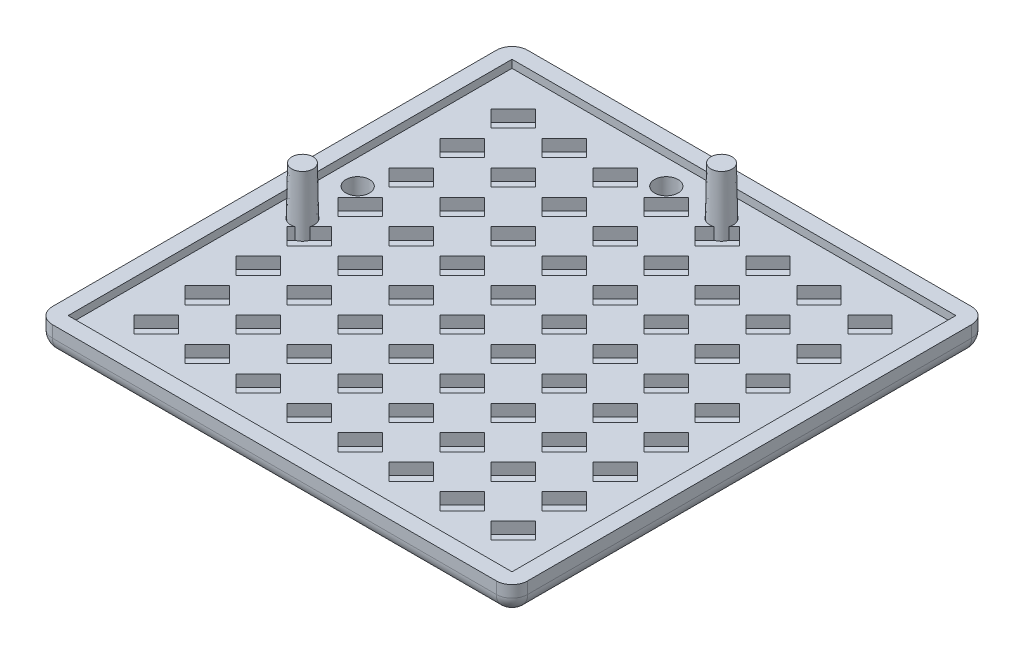
SolidWorks part; units mm, degrees
ref_plane "Front Plane" through (0, 0, 0) normal (0, 0, 1) x (1, 0, 0)
ref_plane "Top Plane" through (0, 0, 0) normal (0, 1, 0) x (1, 0, 0)
ref_plane "Right Plane" through (0, 0, 0) normal (1, 0, 0) x (0, 0, -1)
sketch "Sketch1" plane through (0, 0, 0) normal (0, 1, 0) x (1, 0, 0)
  line L1 (-30.3, -30.3) -> (30.3, -30.3)
  line L2 (-30.3, -30.3) -> (-30.3, 30.3)
  line L3 (-30.3, 30.3) -> (30.3, 30.3)
  line L4 (30.3, -30.3) -> (30.3, 30.3)
  line L5 (-30.3, -30.3) -> (30.3, 30.3) construction
  line L6 (-30.3, 30.3) -> (30.3, -30.3) construction
  point P0 (0, 0)
  dimension "D1" = 60.6
  dimension "D2" = 60.6
extrude "Boss-Extrude1" add sketch "Sketch1" along normal blind 3.5
sketch "led" plane through (0, 0, 0) normal (0, -1, 0) x (1, 0, 0)
  line L0 (30.3, -30.3) -> (-30.3, 30.3) construction
  line L1 (-30.3, 30.3) -> (-30.3, -30.3) construction
  line L2 (-30.3, -30.3) -> (30.3, 30.3) construction
  line L3 (22.4716, -20.3503) -> (25.3, -23.1787)
  line L4 (22.4716, -20.3503) -> (20.3503, -22.4716)
  line L5 (25.3, -23.1787) -> (23.1787, -25.3)
  line L6 (20.3503, -22.4716) -> (23.1787, -25.3)
  line L7 (22.4716, -20.3503) -> (23.1787, -25.3) construction
  line L8 (25.3, -23.1787) -> (20.3503, -22.4716) construction
  line L11 (30.3, 30.3) -> (30.3, -30.3) construction
  line L13 (13.8503, -22.4716) -> (16.6787, -25.3)
  line L14 (15.9716, -20.3503) -> (18.8, -23.1787)
  line L15 (15.9716, -20.3503) -> (13.8503, -22.4716)
  line L16 (18.8, -23.1787) -> (16.6787, -25.3)
  line L17 (7.3503, -22.4716) -> (10.1787, -25.3)
  line L18 (9.4716, -20.3503) -> (12.3, -23.1787)
  line L19 (9.4716, -20.3503) -> (7.3503, -22.4716)
  line L20 (12.3, -23.1787) -> (10.1787, -25.3)
  line L21 (0.8503, -22.4716) -> (3.6787, -25.3)
  line L22 (2.9716, -20.3503) -> (5.8, -23.1787)
  line L23 (2.9716, -20.3503) -> (0.8503, -22.4716)
  line L24 (5.8, -23.1787) -> (3.6787, -25.3)
  line L25 (-5.6497, -22.4716) -> (-2.8213, -25.3)
  line L26 (-3.5284, -20.3503) -> (-0.7, -23.1787)
  line L27 (-3.5284, -20.3503) -> (-5.6497, -22.4716)
  line L28 (-0.7, -23.1787) -> (-2.8213, -25.3)
  line L29 (-12.1497, -22.4716) -> (-9.3213, -25.3)
  line L30 (-10.0284, -20.3503) -> (-7.2, -23.1787)
  line L31 (-10.0284, -20.3503) -> (-12.1497, -22.4716)
  line L32 (-7.2, -23.1787) -> (-9.3213, -25.3)
  line L33 (-18.6497, -22.4716) -> (-15.8213, -25.3)
  line L34 (-16.5284, -20.3503) -> (-13.7, -23.1787)
  line L35 (-16.5284, -20.3503) -> (-18.6497, -22.4716)
  line L36 (-13.7, -23.1787) -> (-15.8213, -25.3)
  line L37 (-25.1497, -22.4716) -> (-22.3213, -25.3)
  line L38 (-23.0284, -20.3503) -> (-20.2, -23.1787)
  line L39 (-23.0284, -20.3503) -> (-25.1497, -22.4716)
  line L40 (-20.2, -23.1787) -> (-22.3213, -25.3)
  line L41 (13.8503, -15.9716) -> (16.6787, -18.8)
  line L42 (15.9716, -13.8503) -> (18.8, -16.6787)
  line L43 (15.9716, -13.8503) -> (13.8503, -15.9716)
  line L44 (18.8, -16.6787) -> (16.6787, -18.8)
  line L45 (7.3503, -15.9716) -> (10.1787, -18.8)
  line L46 (9.4716, -13.8503) -> (12.3, -16.6787)
  line L47 (9.4716, -13.8503) -> (7.3503, -15.9716)
  line L48 (12.3, -16.6787) -> (10.1787, -18.8)
  line L49 (0.8503, -15.9716) -> (3.6787, -18.8)
  line L50 (2.9716, -13.8503) -> (5.8, -16.6787)
  line L51 (2.9716, -13.8503) -> (0.8503, -15.9716)
  line L52 (5.8, -16.6787) -> (3.6787, -18.8)
  line L53 (-5.6497, -15.9716) -> (-2.8213, -18.8)
  line L54 (-3.5284, -13.8503) -> (-0.7, -16.6787)
  line L55 (-3.5284, -13.8503) -> (-5.6497, -15.9716)
  line L56 (-0.7, -16.6787) -> (-2.8213, -18.8)
  line L57 (-12.1497, -15.9716) -> (-9.3213, -18.8)
  line L58 (-10.0284, -13.8503) -> (-7.2, -16.6787)
  line L59 (-10.0284, -13.8503) -> (-12.1497, -15.9716)
  line L60 (-7.2, -16.6787) -> (-9.3213, -18.8)
  line L61 (-18.6497, -15.9716) -> (-15.8213, -18.8)
  line L62 (-16.5284, -13.8503) -> (-13.7, -16.6787)
  line L63 (-16.5284, -13.8503) -> (-18.6497, -15.9716)
  line L64 (-13.7, -16.6787) -> (-15.8213, -18.8)
  line L65 (-25.1497, -15.9716) -> (-22.3213, -18.8)
  line L66 (-23.0284, -13.8503) -> (-20.2, -16.6787)
  line L67 (-23.0284, -13.8503) -> (-25.1497, -15.9716)
  line L68 (-20.2, -16.6787) -> (-22.3213, -18.8)
  line L69 (13.8503, -9.4716) -> (16.6787, -12.3)
  line L70 (15.9716, -7.3503) -> (18.8, -10.1787)
  line L71 (15.9716, -7.3503) -> (13.8503, -9.4716)
  line L72 (18.8, -10.1787) -> (16.6787, -12.3)
  line L73 (7.3503, -9.4716) -> (10.1787, -12.3)
  line L74 (9.4716, -7.3503) -> (12.3, -10.1787)
  line L75 (9.4716, -7.3503) -> (7.3503, -9.4716)
  line L76 (12.3, -10.1787) -> (10.1787, -12.3)
  line L77 (0.8503, -9.4716) -> (3.6787, -12.3)
  line L78 (2.9716, -7.3503) -> (5.8, -10.1787)
  line L79 (2.9716, -7.3503) -> (0.8503, -9.4716)
  line L80 (5.8, -10.1787) -> (3.6787, -12.3)
  line L81 (-5.6497, -9.4716) -> (-2.8213, -12.3)
  line L82 (-3.5284, -7.3503) -> (-0.7, -10.1787)
  line L83 (-3.5284, -7.3503) -> (-5.6497, -9.4716)
  line L84 (-0.7, -10.1787) -> (-2.8213, -12.3)
  line L85 (-12.1497, -9.4716) -> (-9.3213, -12.3)
  line L86 (-10.0284, -7.3503) -> (-7.2, -10.1787)
  line L87 (-10.0284, -7.3503) -> (-12.1497, -9.4716)
  line L88 (-7.2, -10.1787) -> (-9.3213, -12.3)
  line L89 (-18.6497, -9.4716) -> (-15.8213, -12.3)
  line L90 (-16.5284, -7.3503) -> (-13.7, -10.1787)
  line L91 (-16.5284, -7.3503) -> (-18.6497, -9.4716)
  line L92 (-13.7, -10.1787) -> (-15.8213, -12.3)
  line L93 (-25.1497, -9.4716) -> (-22.3213, -12.3)
  line L94 (-23.0284, -7.3503) -> (-20.2, -10.1787)
  line L95 (-23.0284, -7.3503) -> (-25.1497, -9.4716)
  line L96 (-20.2, -10.1787) -> (-22.3213, -12.3)
  line L97 (13.8503, -2.9716) -> (16.6787, -5.8)
  line L98 (15.9716, -0.8503) -> (18.8, -3.6787)
  line L99 (15.9716, -0.8503) -> (13.8503, -2.9716)
  line L100 (18.8, -3.6787) -> (16.6787, -5.8)
  line L101 (7.3503, -2.9716) -> (10.1787, -5.8)
  line L102 (9.4716, -0.8503) -> (12.3, -3.6787)
  line L103 (9.4716, -0.8503) -> (7.3503, -2.9716)
  line L104 (12.3, -3.6787) -> (10.1787, -5.8)
  line L105 (0.8503, -2.9716) -> (3.6787, -5.8)
  line L106 (2.9716, -0.8503) -> (5.8, -3.6787)
  line L107 (2.9716, -0.8503) -> (0.8503, -2.9716)
  line L108 (5.8, -3.6787) -> (3.6787, -5.8)
  line L109 (-5.6497, -2.9716) -> (-2.8213, -5.8)
  line L110 (-3.5284, -0.8503) -> (-0.7, -3.6787)
  line L111 (-3.5284, -0.8503) -> (-5.6497, -2.9716)
  line L112 (-0.7, -3.6787) -> (-2.8213, -5.8)
  line L113 (-12.1497, -2.9716) -> (-9.3213, -5.8)
  line L114 (-10.0284, -0.8503) -> (-7.2, -3.6787)
  line L115 (-10.0284, -0.8503) -> (-12.1497, -2.9716)
  line L116 (-7.2, -3.6787) -> (-9.3213, -5.8)
  line L117 (-18.6497, -2.9716) -> (-15.8213, -5.8)
  line L118 (-16.5284, -0.8503) -> (-13.7, -3.6787)
  line L119 (-16.5284, -0.8503) -> (-18.6497, -2.9716)
  line L120 (-13.7, -3.6787) -> (-15.8213, -5.8)
  line L121 (-25.1497, -2.9716) -> (-22.3213, -5.8)
  line L122 (-23.0284, -0.8503) -> (-20.2, -3.6787)
  line L123 (-23.0284, -0.8503) -> (-25.1497, -2.9716)
  line L124 (-20.2, -3.6787) -> (-22.3213, -5.8)
  line L125 (13.8503, 3.5284) -> (16.6787, 0.7)
  line L126 (15.9716, 5.6497) -> (18.8, 2.8213)
  line L127 (15.9716, 5.6497) -> (13.8503, 3.5284)
  line L128 (18.8, 2.8213) -> (16.6787, 0.7)
  line L129 (7.3503, 3.5284) -> (10.1787, 0.7)
  line L130 (9.4716, 5.6497) -> (12.3, 2.8213)
  line L131 (9.4716, 5.6497) -> (7.3503, 3.5284)
  line L132 (12.3, 2.8213) -> (10.1787, 0.7)
  line L133 (0.8503, 3.5284) -> (3.6787, 0.7)
  line L134 (2.9716, 5.6497) -> (5.8, 2.8213)
  line L135 (2.9716, 5.6497) -> (0.8503, 3.5284)
  line L136 (5.8, 2.8213) -> (3.6787, 0.7)
  line L137 (-5.6497, 3.5284) -> (-2.8213, 0.7)
  line L138 (-3.5284, 5.6497) -> (-0.7, 2.8213)
  line L139 (-3.5284, 5.6497) -> (-5.6497, 3.5284)
  line L140 (-0.7, 2.8213) -> (-2.8213, 0.7)
  line L141 (-12.1497, 3.5284) -> (-9.3213, 0.7)
  line L142 (-10.0284, 5.6497) -> (-7.2, 2.8213)
  line L143 (-10.0284, 5.6497) -> (-12.1497, 3.5284)
  line L144 (-7.2, 2.8213) -> (-9.3213, 0.7)
  line L145 (-18.6497, 3.5284) -> (-15.8213, 0.7)
  line L146 (-16.5284, 5.6497) -> (-13.7, 2.8213)
  line L147 (-16.5284, 5.6497) -> (-18.6497, 3.5284)
  line L148 (-13.7, 2.8213) -> (-15.8213, 0.7)
  line L149 (-25.1497, 3.5284) -> (-22.3213, 0.7)
  line L150 (-23.0284, 5.6497) -> (-20.2, 2.8213)
  line L151 (-23.0284, 5.6497) -> (-25.1497, 3.5284)
  line L152 (-20.2, 2.8213) -> (-22.3213, 0.7)
  line L153 (13.8503, 10.0284) -> (16.6787, 7.2)
  line L154 (15.9716, 12.1497) -> (18.8, 9.3213)
  line L155 (15.9716, 12.1497) -> (13.8503, 10.0284)
  line L156 (18.8, 9.3213) -> (16.6787, 7.2)
  line L157 (7.3503, 10.0284) -> (10.1787, 7.2)
  line L158 (9.4716, 12.1497) -> (12.3, 9.3213)
  line L159 (9.4716, 12.1497) -> (7.3503, 10.0284)
  line L160 (12.3, 9.3213) -> (10.1787, 7.2)
  line L161 (0.8503, 10.0284) -> (3.6787, 7.2)
  line L162 (2.9716, 12.1497) -> (5.8, 9.3213)
  line L163 (2.9716, 12.1497) -> (0.8503, 10.0284)
  line L164 (5.8, 9.3213) -> (3.6787, 7.2)
  line L165 (-5.6497, 10.0284) -> (-2.8213, 7.2)
  line L166 (-3.5284, 12.1497) -> (-0.7, 9.3213)
  line L167 (-3.5284, 12.1497) -> (-5.6497, 10.0284)
  line L168 (-0.7, 9.3213) -> (-2.8213, 7.2)
  line L169 (-12.1497, 10.0284) -> (-9.3213, 7.2)
  line L170 (-10.0284, 12.1497) -> (-7.2, 9.3213)
  line L171 (-10.0284, 12.1497) -> (-12.1497, 10.0284)
  line L172 (-7.2, 9.3213) -> (-9.3213, 7.2)
  line L173 (-18.6497, 10.0284) -> (-15.8213, 7.2)
  line L174 (-16.5284, 12.1497) -> (-13.7, 9.3213)
  line L175 (-16.5284, 12.1497) -> (-18.6497, 10.0284)
  line L176 (-13.7, 9.3213) -> (-15.8213, 7.2)
  line L177 (-25.1497, 10.0284) -> (-22.3213, 7.2)
  line L178 (-23.0284, 12.1497) -> (-20.2, 9.3213)
  line L179 (-23.0284, 12.1497) -> (-25.1497, 10.0284)
  line L180 (-20.2, 9.3213) -> (-22.3213, 7.2)
  line L181 (13.8503, 16.5284) -> (16.6787, 13.7)
  line L182 (15.9716, 18.6497) -> (18.8, 15.8213)
  line L183 (15.9716, 18.6497) -> (13.8503, 16.5284)
  line L184 (18.8, 15.8213) -> (16.6787, 13.7)
  line L185 (7.3503, 16.5284) -> (10.1787, 13.7)
  line L186 (9.4716, 18.6497) -> (12.3, 15.8213)
  line L187 (9.4716, 18.6497) -> (7.3503, 16.5284)
  line L188 (12.3, 15.8213) -> (10.1787, 13.7)
  line L189 (0.8503, 16.5284) -> (3.6787, 13.7)
  line L190 (2.9716, 18.6497) -> (5.8, 15.8213)
  line L191 (2.9716, 18.6497) -> (0.8503, 16.5284)
  line L192 (5.8, 15.8213) -> (3.6787, 13.7)
  line L193 (-5.6497, 16.5284) -> (-2.8213, 13.7)
  line L194 (-3.5284, 18.6497) -> (-0.7, 15.8213)
  line L195 (-3.5284, 18.6497) -> (-5.6497, 16.5284)
  line L196 (-0.7, 15.8213) -> (-2.8213, 13.7)
  line L197 (-12.1497, 16.5284) -> (-9.3213, 13.7)
  line L198 (-10.0284, 18.6497) -> (-7.2, 15.8213)
  line L199 (-10.0284, 18.6497) -> (-12.1497, 16.5284)
  line L200 (-7.2, 15.8213) -> (-9.3213, 13.7)
  line L201 (-18.6497, 16.5284) -> (-15.8213, 13.7)
  line L202 (-16.5284, 18.6497) -> (-13.7, 15.8213)
  line L203 (-16.5284, 18.6497) -> (-18.6497, 16.5284)
  line L204 (-13.7, 15.8213) -> (-15.8213, 13.7)
  line L205 (-25.1497, 16.5284) -> (-22.3213, 13.7)
  line L206 (-23.0284, 18.6497) -> (-20.2, 15.8213)
  line L207 (-23.0284, 18.6497) -> (-25.1497, 16.5284)
  line L208 (-20.2, 15.8213) -> (-22.3213, 13.7)
  line L209 (13.8503, 23.0284) -> (16.6787, 20.2)
  line L210 (15.9716, 25.1497) -> (18.8, 22.3213)
  line L211 (15.9716, 25.1497) -> (13.8503, 23.0284)
  line L212 (18.8, 22.3213) -> (16.6787, 20.2)
  line L213 (7.3503, 23.0284) -> (10.1787, 20.2)
  line L214 (9.4716, 25.1497) -> (12.3, 22.3213)
  line L215 (9.4716, 25.1497) -> (7.3503, 23.0284)
  line L216 (12.3, 22.3213) -> (10.1787, 20.2)
  line L217 (0.8503, 23.0284) -> (3.6787, 20.2)
  line L218 (2.9716, 25.1497) -> (5.8, 22.3213)
  line L219 (2.9716, 25.1497) -> (0.8503, 23.0284)
  line L220 (5.8, 22.3213) -> (3.6787, 20.2)
  line L221 (-5.6497, 23.0284) -> (-2.8213, 20.2)
  line L222 (-3.5284, 25.1497) -> (-0.7, 22.3213)
  line L223 (-3.5284, 25.1497) -> (-5.6497, 23.0284)
  line L224 (-0.7, 22.3213) -> (-2.8213, 20.2)
  line L225 (-12.1497, 23.0284) -> (-9.3213, 20.2)
  line L226 (-10.0284, 25.1497) -> (-7.2, 22.3213)
  line L227 (-10.0284, 25.1497) -> (-12.1497, 23.0284)
  line L228 (-7.2, 22.3213) -> (-9.3213, 20.2)
  line L229 (-18.6497, 23.0284) -> (-15.8213, 20.2)
  line L230 (-16.5284, 25.1497) -> (-13.7, 22.3213)
  line L231 (-16.5284, 25.1497) -> (-18.6497, 23.0284)
  line L232 (-13.7, 22.3213) -> (-15.8213, 20.2)
  line L233 (-25.1497, 23.0284) -> (-22.3213, 20.2)
  line L234 (-23.0284, 25.1497) -> (-20.2, 22.3213)
  line L235 (-23.0284, 25.1497) -> (-25.1497, 23.0284)
  line L236 (-20.2, 22.3213) -> (-22.3213, 20.2)
  line L237 (20.3503, -15.9716) -> (23.1787, -18.8)
  line L238 (22.4716, -13.8503) -> (25.3, -16.6787)
  line L239 (22.4716, -13.8503) -> (20.3503, -15.9716)
  line L240 (25.3, -16.6787) -> (23.1787, -18.8)
  line L241 (20.3503, -9.4716) -> (23.1787, -12.3)
  line L242 (22.4716, -7.3503) -> (25.3, -10.1787)
  line L243 (22.4716, -7.3503) -> (20.3503, -9.4716)
  line L244 (25.3, -10.1787) -> (23.1787, -12.3)
  line L245 (20.3503, -2.9716) -> (23.1787, -5.8)
  line L246 (22.4716, -0.8503) -> (25.3, -3.6787)
  line L247 (22.4716, -0.8503) -> (20.3503, -2.9716)
  line L248 (25.3, -3.6787) -> (23.1787, -5.8)
  line L249 (20.3503, 3.5284) -> (23.1787, 0.7)
  line L250 (22.4716, 5.6497) -> (25.3, 2.8213)
  line L251 (22.4716, 5.6497) -> (20.3503, 3.5284)
  line L252 (25.3, 2.8213) -> (23.1787, 0.7)
  line L253 (20.3503, 10.0284) -> (23.1787, 7.2)
  line L254 (22.4716, 12.1497) -> (25.3, 9.3213)
  line L255 (22.4716, 12.1497) -> (20.3503, 10.0284)
  line L256 (25.3, 9.3213) -> (23.1787, 7.2)
  line L257 (20.3503, 16.5284) -> (23.1787, 13.7)
  line L258 (22.4716, 18.6497) -> (25.3, 15.8213)
  line L259 (22.4716, 18.6497) -> (20.3503, 16.5284)
  line L260 (25.3, 15.8213) -> (23.1787, 13.7)
  line L261 (20.3503, 23.0284) -> (23.1787, 20.2)
  line L262 (22.4716, 25.1497) -> (25.3, 22.3213)
  line L263 (22.4716, 25.1497) -> (20.3503, 23.0284)
  line L264 (25.3, 22.3213) -> (23.1787, 20.2)
  point P9 (22.8251, -22.8251)
  dimension "D1" = 4
  dimension "D2" = 3
  dimension "D3" = 5
  dimension "D4" = 8
  dimension "D5" = 8
extrude "Cut-Extrude1" cut sketch "led" against normal through all from offset 1 offset against normal yes
sketch "Sketch3" plane through (0, 3.5, 0) normal (0, 1, 0) x (1, 0, 0)
  line L0 (30.3, 30.3) -> (-30.3, 30.3) construction
  line L1 (28.3, -28.3) -> (-28.3, -28.3)
  line L2 (28.3, -28.3) -> (28.3, 28.3)
  line L3 (28.3, 28.3) -> (-28.3, 28.3)
  line L4 (-28.3, -28.3) -> (-28.3, 28.3)
  line L5 (28.3, -28.3) -> (-28.3, 28.3) construction
  line L6 (28.3, 28.3) -> (-28.3, -28.3) construction
  line L7 (-30.3, 30.3) -> (-30.3, -30.3) construction
  point P0 (0, 0)
  dimension "D1" = 2
  dimension "D2" = 2
extrude "Cut-Extrude2" cut sketch "Sketch3" along normal through all from offset 1 offset against normal yes
sketch "Sketch4" plane through (0, 3.5, 0) normal (0, 1, 0) x (1, 0, 0)
  line L0 (-30.3, 30.3) -> (30.3, -30.3) construction
  line L2 (30.3, 30.3) -> (-30.3, 30.3) construction
  line L3 (1.6, 25.12) -> (-5.44, 25.12) construction
  line L4 (-30.3, 30.3) -> (-30.3, -30.3) construction
  circle A0 centre (1.6, 25.12) radius 1.5
  circle A1 centre (-5.44, 25.12) radius 1.5
  circle A2 centre (-25.12, 5.44) radius 1.5
  circle A3 centre (-25.12, -1.6) radius 1.5
  dimension "D1" = 3
  dimension "D2" = 3
  dimension "D3" = 31.9
  dimension "D4" = 7.04
  dimension "D5" = 5.18
extrude "Cut-Extrude3" cut sketch "Sketch4" against normal through all
sketch "Sketch5" plane through (0, 3.5, 0) normal (0, 1, 0) x (1, 0, 0)
  line L0 (-30.3, 30.3) -> (30.3, -30.3) construction
  circle A0 centre (-25.12, -1.6) radius 1.5
  circle A1 centre (-25.12, -1.6) radius 1.5 construction
  circle A2 centre (1.6, 25.12) radius 1.5
  dimension "D1" = 3
extrude "Boss-Extrude3" add sketch "Sketch5" along normal blind 8.6 draft 1 from surface at -3.5 separate body starting at face at (1.6, 0, -23.62)
fillet "Fillet3" radius 2 4 edges at (-30.3, 1.75, 30.3) (-30.3, 1.75, -30.3) (30.3, 1.75, -30.3) (30.3, 1.75, 30.3)
fillet "Fillet4" radius 2 8 edges at (-29.7142, 0, 29.7142) (-30.3, 0, 0) (-29.7142, 0, -29.7142) (0, 0, -30.3) (29.7142, 0, -29.7142) (30.3, 0, 0) (29.7142, 0, 29.7142) (0, 0, 30.3)
